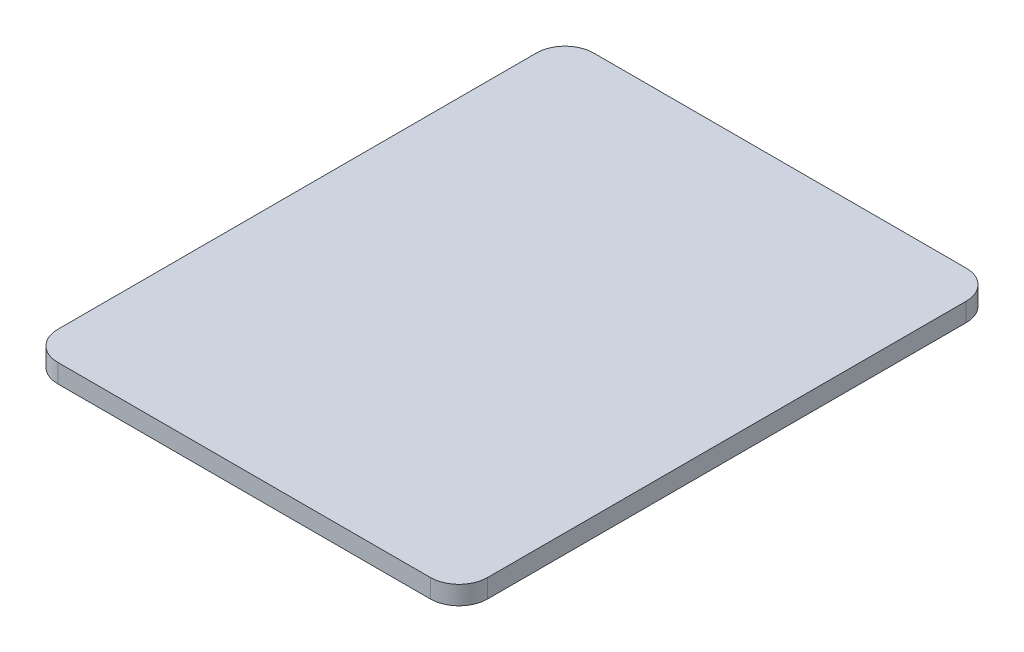
SolidWorks part; units mm, degrees
ref_plane "前视基准面" through (0, 0, 0) normal (0, 0, 1) x (1, 0, 0)
ref_plane "上视基准面" through (0, 0, 0) normal (0, 1, 0) x (1, 0, 0)
ref_plane "右视基准面" through (0, 0, 0) normal (1, 0, 0) x (0, 0, -1)
sketch "草图1" plane through (0, 0, 0) normal (0, 1, 0) x (1, 0, 0)
  line L1 (-15, 18.7) -> (15, 18.7)
  line L2 (-15, 18.7) -> (-15, -18.7)
  line L3 (-15, -18.7) -> (15, -18.7)
  line L4 (15, 18.7) -> (15, -18.7)
  line L5 (-15, 18.7) -> (15, -18.7) construction
  line L6 (-15, -18.7) -> (15, 18.7) construction
  point P0 (0, 0)
  dimension "D1" = 30
  dimension "D2" = 37.4
extrude "凸台-拉伸1" add sketch "草图1" along normal blind 1.3
fillet "圆角1" radius 2 4 edges at (-15, 0.65, -18.7) (15, 0.65, -18.7) (15, 0.65, 18.7) (-15, 0.65, 18.7)
